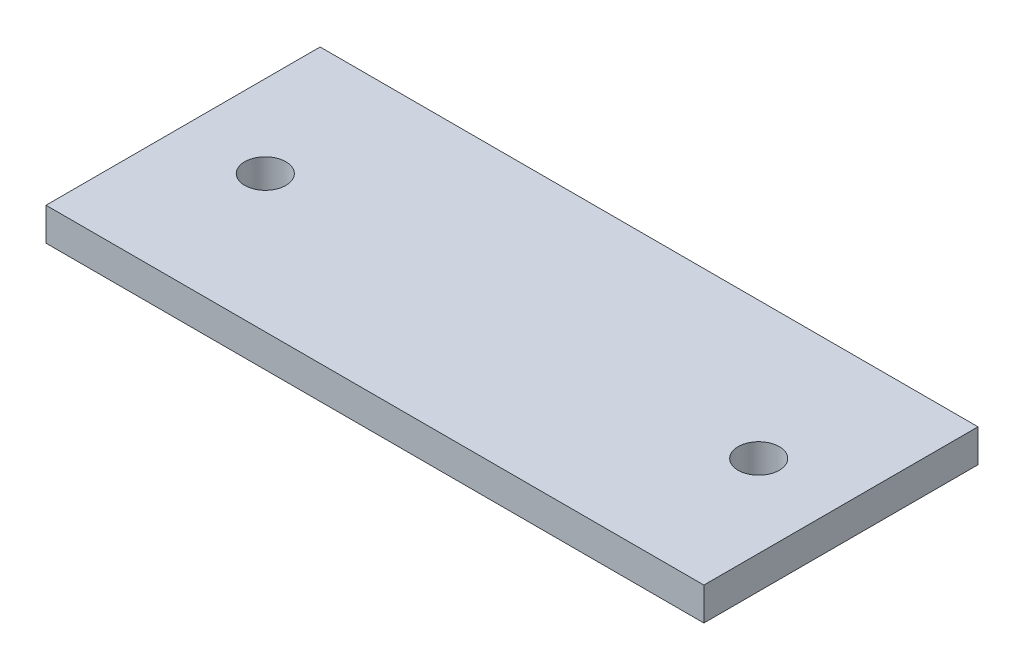
SolidWorks part; units mm, degrees
material "6061-T6 (SS)"
ref_plane "Front Plane" through (0, 0, 0) normal (0, 0, 1) x (1, 0, 0)
ref_plane "Top Plane" through (0, 0, 0) normal (0, 1, 0) x (1, 0, 0)
ref_plane "Right Plane" through (0, 0, 0) normal (1, 0, 0) x (0, 0, -1)
sketch "Sketch2" plane through (0, 0, 0) normal (0, 1, 0) x (1, 0, 0)
  line L1 (0, 0) -> (304.8, 0)
  line L2 (0, 0) -> (0, -127)
  line L3 (0, -127) -> (304.8, -127)
  line L4 (304.8, 0) -> (304.8, -127)
  circle A0 centre (38.1, -63.5) radius 9.525
  circle A1 centre (266.7, -63.5) radius 9.525
  point P13 (0, -63.5)
  point P14 (304.8, -63.5)
  dimension "D3" = 19.05
  dimension "D4" = 19.05
  dimension "D1" = 304.8
  dimension "D2" = 127
  dimension "D5" = 38.1
  dimension "D6" = 38.1
extrude "Boss-Extrude1" add sketch "Sketch2" along normal blind 15.24
equation "\"t\"= 5in'Thickness (in)"
equation "\"L\"= 12in'Length (in)"
equation "\"Dis\"= 9in'Distance between holes(In)"
equation "\"D\"= .75in'Diameter(In)"
equation "\"F\"= 224.809'Load (lbs)"
equation "\"C\"= 1.5in'Distance from hole to end(in)"
equation "\"E\"= 10 * 10 ^ 6'Modulus of Elastisity (PSI)"
equation "\"Y\"= .003937in'max deflection(In)"
equation "\"H\"= .6'Hight (in)"
equation "\"D1@Sketch2\"=\"L\""
equation "\"D2@Sketch2\"=\"t\""
equation "\"D5@Sketch2\"=\"C\""
equation "\"D6@Sketch2\"=\"C\""
equation "\"D1@Boss-Extrude1\"=\"H\""
